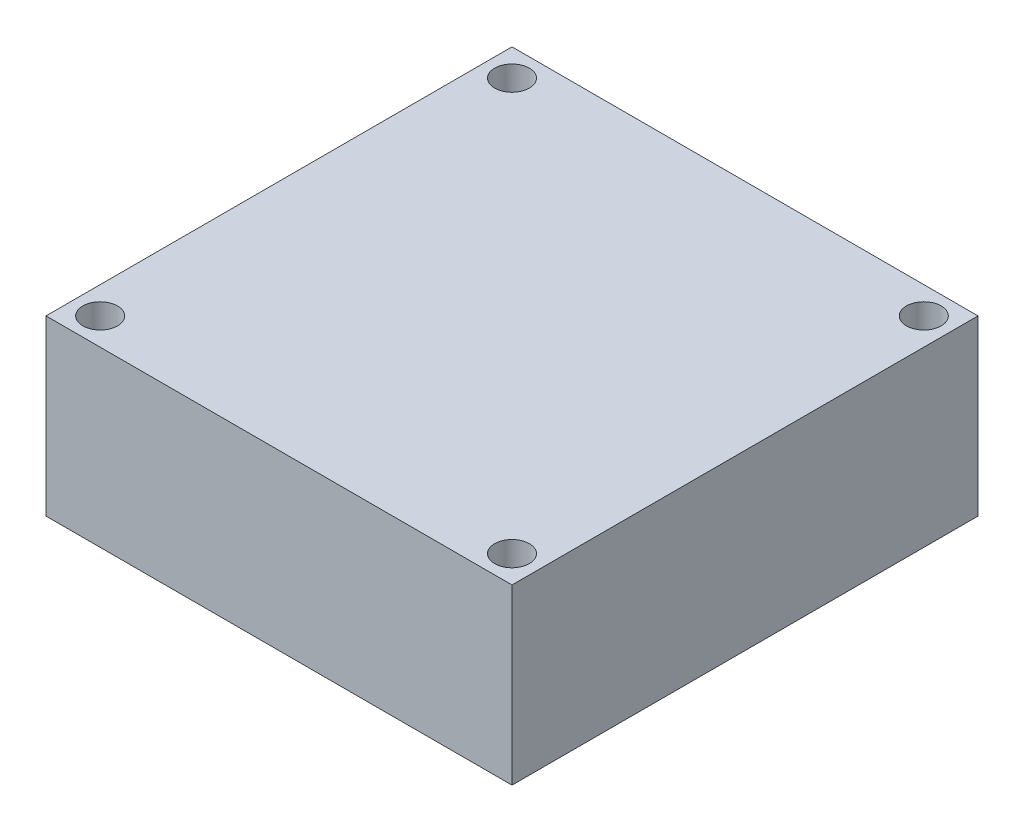
SolidWorks part; units mm, degrees
ref_plane "Front Plane" through (0, 0, 0) normal (0, 0, 1) x (1, 0, 0)
ref_plane "Top Plane" through (0, 0, 0) normal (0, 1, 0) x (1, 0, 0)
ref_plane "Right Plane" through (0, 0, 0) normal (1, 0, 0) x (0, 0, -1)
sketch "Sketch1" plane through (0, 0, 0) normal (0, 1, 0) x (1, 0, 0)
  line L1 (-21.5, -21.5) -> (21.5, -21.5)
  line L2 (-21.5, -21.5) -> (-21.5, 21.5)
  line L3 (-21.5, 21.5) -> (21.5, 21.5)
  line L4 (21.5, -21.5) -> (21.5, 21.5)
  line L5 (-21.5, -21.5) -> (21.5, 21.5) construction
  line L6 (-21.5, 21.5) -> (21.5, -21.5) construction
  point P0 (0, 0)
  dimension "D1" = 43
  dimension "D2" = 43
extrude "Boss-Extrude1" add sketch "Sketch1" along normal blind 16
sketch "Sketch4" plane through (0, 16, 0) normal (0, 1, 0) x (1, 0, 0)
  line L1 (-19, -19) -> (19, -19) construction
  line L2 (-19, -19) -> (-19, 19) construction
  line L3 (-19, 19) -> (19, 19) construction
  line L4 (19, -19) -> (19, 19) construction
  line L5 (-19, -19) -> (19, 19) construction
  line L6 (-19, 19) -> (19, -19) construction
  point P0 (0, 0)
  dimension "D1" = 38
  dimension "D2" = 38
hole_wizard "M3 Clearance Hole1" positions "Sketch5" profile "Sketch6" hole size "M3" standard "ANSI Metric" end condition through all
sketch "Sketch5" plane through (0, 16, 0) normal (0, 1, 0) x (1, 0, 0)
  point P0 (-19, 19)
  point P3 (19, 19)
  point P6 (19, -19)
  point P9 (-19, -19)
sketch "Sketch6" plane through (-19, 16, -19) normal (1, 0, 0) x (0, 0, 1)
  line L0 (0, 0) -> (0, 16)
  line L1 (0, 16) -> (1.6, 16)
  line L2 (1.6, 16) -> (1.6, 0)
  line L5 (1.6, 0) -> (0, 0)
  line L11 (0, -6.35) -> (0, 107.95) construction
  dimension "Thru Hole Dia." = 3.2
  dimension "Thru Hole Depth" = 16
